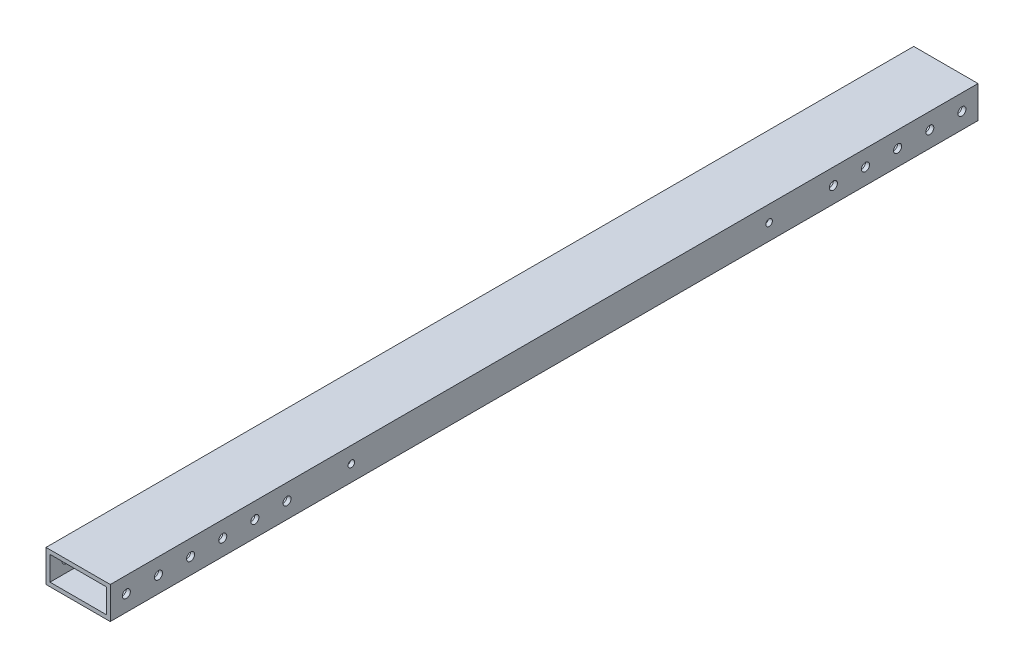
SolidWorks part; units mm, degrees
material "6061 Alloy"
ref_plane "Front Plane" through (0, 0, 0) normal (0, 0, 1) x (1, 0, 0)
ref_plane "Top Plane" through (0, 0, 0) normal (0, 1, 0) x (1, 0, 0)
ref_plane "Right Plane" through (0, 0, 0) normal (1, 0, 0) x (0, 0, -1)
sketch "Sketch1" plane through (0, 0, 0) normal (0, 0, 1) x (1, 0, 0)
  line L0 (-22.225, 9.525) -> (22.225, 9.525)
  line L2 (-25.4, 12.7) -> (25.4, 12.7)
  line L3 (-25.4, 12.7) -> (-25.4, -12.7)
  line L4 (-25.4, -12.7) -> (25.4, -12.7)
  line L5 (25.4, 12.7) -> (25.4, -12.7)
  line L10 (22.225, 9.525) -> (22.225, -9.525)
  line L11 (-22.225, -9.525) -> (22.225, -9.525)
  line L12 (-22.225, 9.525) -> (-22.225, -9.525)
  point P12 (0, 12.7)
  point P14 (25.4, 0)
  dimension "Wall Thickness" = 3.175
  dimension "Outside Width" = 50.8
  dimension "Outside Height" = 25.4
  dimension "Inside Height" = 19.05
  dimension "Inside Width" = 44.45
sketch "Sketch2" plane through (0, 0, 0) normal (1, 0, 0) x (0, 0, -1)
  line L0 (342.9, 0) -> (-342.9, 0)
  point P4 (0, 0)
  point P7 (-342.9, 0)
  point P10 (342.9, 0)
  dimension "Length" = 685.8
sketch "Sketch3" plane through (0, 0, 0) normal (0, 0, 1) x (1, 0, 0)
  line L21 (25.4, 12.7) -> (-25.4, 12.7)
  line L22 (25.4, -12.7) -> (25.4, 12.7)
  line L23 (-25.4, -12.7) -> (25.4, -12.7)
  line L24 (-25.4, 12.7) -> (-25.4, -12.7)
  line L25 (25.4, 12.7) -> (-25.4, 12.7)
  line L26 (25.4, -12.7) -> (25.4, 12.7)
  line L27 (-25.4, -12.7) -> (25.4, -12.7)
  line L28 (-25.4, 12.7) -> (-25.4, -12.7)
  line L29 (22.225, 9.525) -> (-22.225, 9.525)
  line L30 (22.225, -9.525) -> (22.225, 9.525)
  line L31 (-22.225, -9.525) -> (22.225, -9.525)
  line L32 (-22.225, 9.525) -> (-22.225, -9.525)
  line L33 (22.225, 9.525) -> (-22.225, 9.525)
  line L34 (22.225, -9.525) -> (22.225, 9.525)
  line L35 (-22.225, -9.525) -> (22.225, -9.525)
  line L36 (-22.225, 9.525) -> (-22.225, -9.525)
  dimension "D1" = 0
  dimension "D2" = 0
extrude "Boss-Extrude1" add sketch "Sketch3" along normal up to vertex (342.9 mm away) and the other way up to vertex (342.9 mm away) up to point (0, 0, 342.9) other way up to point (0, 0, -342.9)
sketch "Drawing Reference" plane through (0, 0, 0) normal (1, 0, 0) x (0, 0, -1)
  line L0 (-342.9, 0) -> (342.9, 0) construction
  line L1 (0, -12.7) -> (0, 12.7) construction
  line L2 (-342.9, -12.7) -> (342.9, -12.7) construction
  line L5 (-342.9, 12.7) -> (342.9, 12.7) construction
  point P7 (-306.324, 0)
  point P8 (306.324, 0)
  dimension "D1" = 36.576
sketch "Sketch5" plane through (25.4, 0, 0) normal (1, 0, 0) x (0, 0, -1)
  line L0 (-342.9, 0) -> (-279.4, 0)
  line L1 (-342.9, -12.7) -> (-342.9, 12.7) construction
  line L2 (-279.4, 0) -> (-254, 0)
  line L3 (-254, 0) -> (-228.6, 0)
  line L4 (-228.6, 0) -> (-203.2, 0)
sketch "Sketch8" plane through (25.4, 0, 0) normal (1, 0, 0) x (0, 0, -1)
  line L0 (342.9, 0) -> (304.8, 0)
  line L1 (342.9, -12.7) -> (342.9, 12.7) construction
  line L2 (304.8, 0) -> (279.4, 0)
  line L3 (279.4, 0) -> (254, 0)
  line L4 (254, 0) -> (228.6, 0)
  line L5 (342.9, 0) -> (330.2, 0)
hole_wizard "1/4 (0.25) Diameter Hole3" positions "Sketch12" profile "Sketch13" hole size "1/4" standard "ANSI Inch" end condition through all
sketch "Sketch12" plane through (-25.4, 0, 0) normal (-1, 0, 0) x (0, 0, 1)
  point P4 (-330.2, 0)
sketch "Sketch13" plane through (-25.4, 0, -330.2) normal (0, 1, 0) x (0, 0, 1)
  line L0 (0, 0) -> (0, 50.8)
  line L1 (0, 50.8) -> (3.175, 50.8)
  line L2 (3.175, 50.8) -> (3.175, 0)
  line L5 (3.175, 0) -> (0, 0)
  line L11 (0, -6.35) -> (0, 107.95) construction
  dimension "Thru Hole Dia." = 6.35
  dimension "Thru Hole Depth" = 50.8
hole_wizard "1/4 (0.25) Diameter Hole4" positions "Sketch14" profile "Sketch15" hole size "1/4" standard "ANSI Inch" end condition through all
sketch "Sketch14" plane through (-25.4, 0, 0) normal (-1, 0, 0) x (0, 0, 1)
  point P0 (304.8, 0)
  point P3 (330.2, 0)
sketch "Sketch15" plane through (-25.4, 0, 304.8) normal (0, 1, 0) x (0, 0, 1)
  line L0 (0, 0) -> (0, 50.8)
  line L1 (0, 50.8) -> (3.175, 50.8)
  line L2 (3.175, 50.8) -> (3.175, 0)
  line L5 (3.175, 0) -> (0, 0)
  line L11 (0, -6.35) -> (0, 107.95) construction
  dimension "Thru Hole Dia." = 6.35
  dimension "Thru Hole Depth" = 50.8
hole_wizard "1/4 (0.25) Diameter Hole5" positions "Sketch17" profile "Sketch18" hole size "1/4" standard "ANSI Inch" end condition through all
sketch "Sketch17" plane through (25.4, 0, 0) normal (1, 0, 0) x (0, 0, -1)
  point P0 (304.8, 0)
  point P3 (279.4, 0)
sketch "Sketch18" plane through (25.4, 0, -304.8) normal (0, 1, 0) x (0, 0, -1)
  line L0 (0, 0) -> (0, 50.8)
  line L1 (0, 50.8) -> (3.175, 50.8)
  line L2 (3.175, 50.8) -> (3.175, 0)
  line L5 (3.175, 0) -> (0, 0)
  line L11 (0, -6.35) -> (0, 107.95) construction
  dimension "Thru Hole Dia." = 6.35
  dimension "Thru Hole Depth" = 50.8
hole_wizard "1/4 (0.25) Diameter Hole6" positions "Sketch19" profile "Sketch20" hole size "1/4" standard "ANSI Inch" end condition through all
sketch "Sketch19" plane through (25.4, 0, 0) normal (1, 0, 0) x (0, 0, -1)
  point P0 (228.6, 0)
  point P3 (254, 0)
sketch "Sketch20" plane through (25.4, 0, -228.6) normal (0, 1, 0) x (0, 0, -1)
  line L0 (0, 0) -> (0, 50.8)
  line L1 (0, 50.8) -> (3.175, 50.8)
  line L2 (3.175, 50.8) -> (3.175, 0)
  line L5 (3.175, 0) -> (0, 0)
  line L11 (0, -6.35) -> (0, 107.95) construction
  dimension "Thru Hole Dia." = 6.35
  dimension "Thru Hole Depth" = 50.8
hole_wizard "1/4 (0.25) Diameter Hole7" positions "Sketch21" profile "Sketch22" hole size "1/4" standard "ANSI Inch" end condition through all
sketch "Sketch21" plane through (25.4, 0, 0) normal (1, 0, 0) x (0, 0, -1)
  point P0 (-203.2, 0)
  point P3 (-228.6, 0)
sketch "Sketch22" plane through (25.4, 0, 203.2) normal (0, 1, 0) x (0, 0, -1)
  line L0 (0, 0) -> (0, 50.8)
  line L1 (0, 50.8) -> (3.175, 50.8)
  line L2 (3.175, 50.8) -> (3.175, 0)
  line L5 (3.175, 0) -> (0, 0)
  line L11 (0, -6.35) -> (0, 107.95) construction
  dimension "Thru Hole Dia." = 6.35
  dimension "Thru Hole Depth" = 50.8
hole_wizard "1/4 (0.25) Diameter Hole8" positions "Sketch23" profile "Sketch24" hole size "1/4" standard "ANSI Inch" end condition through all
sketch "Sketch23" plane through (25.4, 0, 0) normal (1, 0, 0) x (0, 0, -1)
  point P0 (-279.4, 0)
  point P3 (-254, 0)
sketch "Sketch24" plane through (25.4, 0, 279.4) normal (0, 1, 0) x (0, 0, -1)
  line L0 (0, 0) -> (0, 50.8)
  line L1 (0, 50.8) -> (3.175, 50.8)
  line L2 (3.175, 50.8) -> (3.175, 0)
  line L5 (3.175, 0) -> (0, 0)
  line L11 (0, -6.35) -> (0, 107.95) construction
  dimension "Thru Hole Dia." = 6.35
  dimension "Thru Hole Depth" = 50.8
sketch "Sketch25" plane through (25.4, 0, 0) normal (1, 0, 0) x (0, 0, -1)
  line L0 (-203.2, 0) -> (-152.4, 0)
  line L1 (228.6, 0) -> (177.8, 0)
hole_wizard "13/64 (0.20313) Diameter Hole1" positions "Sketch26" profile "Sketch27" hole size "13/64" standard "ANSI Inch" end condition through all
sketch "Sketch26" plane through (25.4, 0, 0) normal (1, 0, 0) x (0, 0, -1)
  point P0 (-152.4, 0)
  point P3 (177.8, 0)
sketch "Sketch27" plane through (25.4, 0, 152.4) normal (0, 1, 0) x (0, 0, -1)
  line L0 (0, 0) -> (0, 50.8)
  line L1 (0, 50.8) -> (2.5798, 50.8)
  line L2 (2.5798, 50.8) -> (2.5798, 0)
  line L5 (2.5798, 0) -> (0, 0)
  line L11 (0, -6.35) -> (0, 107.95) construction
  dimension "Thru Hole Dia." = 5.1595
  dimension "Thru Hole Depth" = 50.8
sketch "Sketch28" plane through (-25.4, 0, 0) normal (-1, 0, 0) x (0, 0, 1)
  line L0 (103.1875, 0) -> (77.7875, 0)
  line L1 (-103.1875, 0) -> (-128.5875, 0)
  point P5 (-128.5875, 0)
  point P6 (-103.1875, 0)
  point P7 (77.7875, 0)
  point P8 (103.1875, 0)
hole_wizard "1/2 (0.5) Diameter Hole1" positions "Sketch29" profile "Sketch30" hole size "1/2" standard "ANSI Inch"
sketch "Sketch29" plane through (-25.4, 0, 0) normal (-1, 0, 0) x (0, 0, 1)
  point P1 (-591.3016, -480.8022)
  point P3 (-103.1875, 0)
  point P6 (77.7875, 0)
  point P9 (103.1875, 0)
  point P13 (-128.5875, 0)
sketch "Sketch30" plane through (-25.4, -480.8022, -591.3016) normal (0, 1, 0) x (0, 0, 1)
  line L0 (0, 0) -> (0, 10.1655)
  line L1 (0, 10.1655) -> (6.35, 6.35)
  line L2 (6.35, 6.35) -> (6.35, 0)
  line L5 (6.35, 0) -> (0, 0)
  line L10 (0, 10.1655) -> (-6.35, 6.35) construction
  line L11 (0, -6.35) -> (0, 107.95) construction
  dimension "Hole Dia." = 12.7
  dimension "Hole Depth" = 6.35
  dimension "Drill Angle" = 118
equation "\"D1@Drawing Reference\"=\"Outside Width@Sketch1\" * 0.72"
